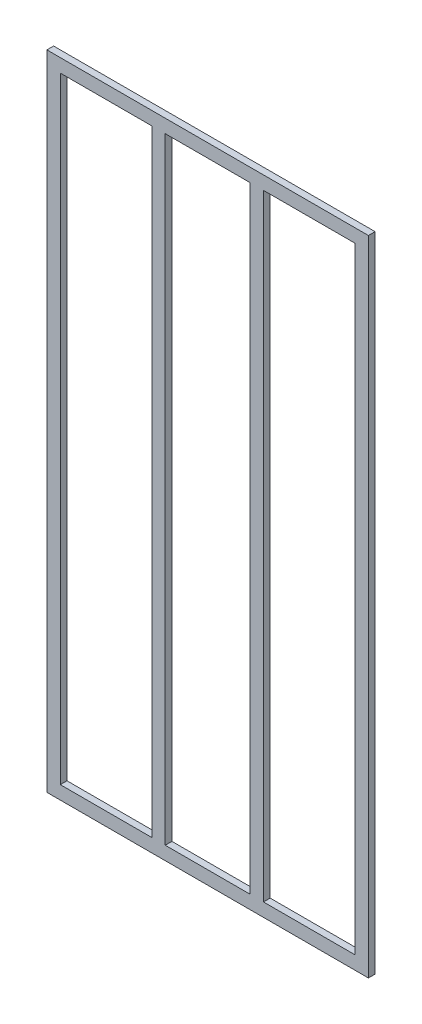
SolidWorks part; units mm, degrees
ref_plane "Alzado" through (0, 0, 0) normal (0, 0, 1) x (1, 0, 0)
ref_plane "Planta" through (0, 0, 0) normal (0, 1, 0) x (1, 0, 0)
ref_plane "Vista lateral" through (0, 0, 0) normal (1, 0, 0) x (0, 0, -1)
sketch "Croquis1" plane through (0, 0, 0) normal (0, 0, 1) x (1, 0, 0)
  line L0 (-559.2, -1169.2) -> (-559.2, 1169.2)
  line L1 (-610, -1220) -> (610, -1220)
  line L2 (-610, -1220) -> (-610, 1220)
  line L3 (-610, 1220) -> (610, 1220)
  line L4 (610, -1220) -> (610, 1220)
  line L5 (-610, -1220) -> (610, 1220) construction
  line L6 (-610, 1220) -> (610, -1220) construction
  line L7 (-559.2, 1169.2) -> (559.2, 1169.2)
  line L8 (559.2, -1169.2) -> (559.2, 1169.2)
  line L9 (-559.2, -1169.2) -> (559.2, -1169.2)
  point P0 (0, 0)
  dimension "D1" = 2440
  dimension "D2" = 1220
  dimension "D3" = 50.8
extrude "Saliente-Extruir1" add sketch "Croquis1" along normal blind 25.4
sketch "Croquis2" plane through (0, 0, 25.4) normal (0, 0, 1) x (1, 0, 0)
  line L0 (-186.4, 1169.2) -> (-186.4, -1169.2) construction
  line L1 (559.2, 1169.2) -> (-559.2, 1169.2) construction
  line L2 (-559.2, -1169.2) -> (559.2, -1169.2) construction
  line L3 (-559.2, 1169.2) -> (-559.2, -1169.2) construction
  line L4 (186.4, 1169.2) -> (186.4, -1169.2) construction
  line L6 (-211.8, -1169.2) -> (-161, -1169.2)
  line L7 (-211.8, -1169.2) -> (-211.8, 1169.2)
  line L8 (-211.8, 1169.2) -> (-161, 1169.2)
  line L9 (-161, -1169.2) -> (-161, 1169.2)
  line L10 (-211.8, -1169.2) -> (-161, 1169.2) construction
  line L11 (-211.8, 1169.2) -> (-161, -1169.2) construction
  line L12 (211.8, -1169.2) -> (161, -1169.2)
  line L13 (211.8, -1169.2) -> (211.8, 1169.2)
  line L14 (211.8, 1169.2) -> (161, 1169.2)
  line L15 (161, -1169.2) -> (161, 1169.2)
  line L16 (211.8, -1169.2) -> (161, 1169.2) construction
  line L17 (211.8, 1169.2) -> (161, -1169.2) construction
  point P10 (-186.4, 0)
  point P15 (186.4, 0)
  dimension "D1" = 372.8
  dimension "D2" = 372.8
  dimension "D3" = 50.8
  dimension "D4" = 50.8
extrude "Saliente-Extruir2" add sketch "Croquis2" against normal blind 25.4
